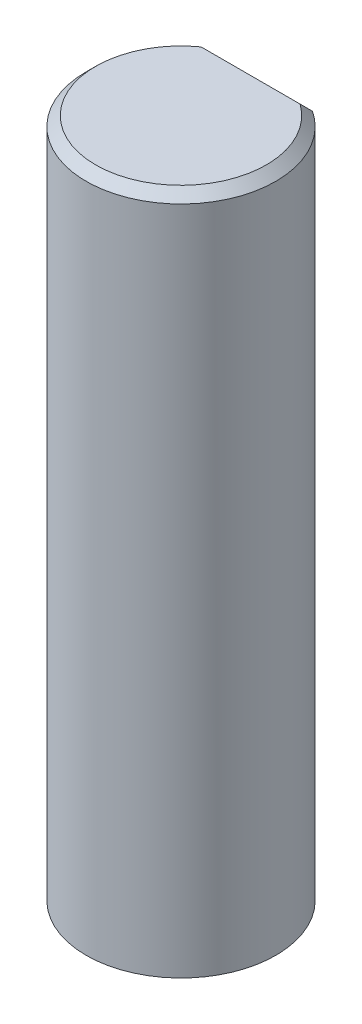
SolidWorks part; units mm, degrees
ref_plane "Alzado" through (0, 0, 0) normal (0, 0, 1) x (1, 0, 0)
ref_plane "Planta" through (0, 0, 0) normal (0, 1, 0) x (1, 0, 0)
ref_plane "Vista lateral" through (0, 0, 0) normal (1, 0, 0) x (0, 0, -1)
sketch "Croquis1" plane through (0, 0, 0) normal (0, 1, 0) x (1, 0, 0)
  circle A0 centre (0, 0) radius 3
  dimension "D1" = 6
extrude "Saliente-Extruir1" add sketch "Croquis1" along normal blind 21.5
sketch "Croquis2" plane through (0, 21.5, 0) normal (0, 1, 0) x (1, 0, 0)
  line L1 (-1.6583, 2.5) -> (1.6583, 2.5)
  circle A0 centre (0, 0) radius 3 construction
  arc A1 (1.6583, 2.5) -> (-1.6583, 2.5) centre (0, 0) ccw
  point P8 (0, 2.5)
  dimension "D1" = 2.5
extrude "Cortar-Extruir1" cut sketch "Croquis2" against normal blind 12
chamfer "Chaflán1" distance 0.3 angle 45 2 edges at (0, 21.5, -2.5) (0, 21.5, 3)
